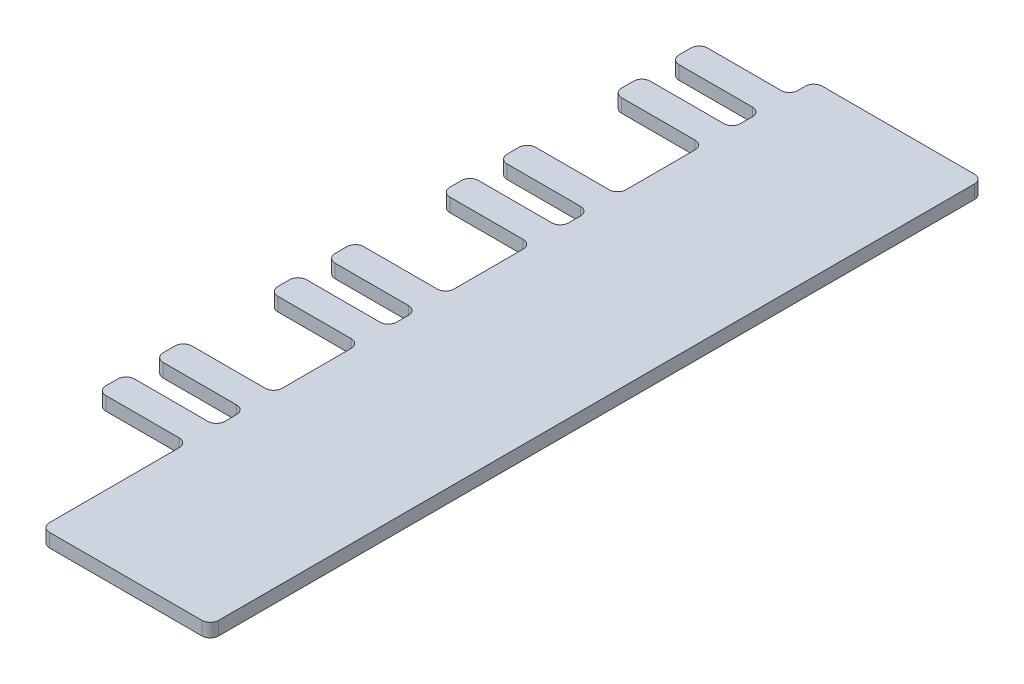
SolidWorks part; units mm, degrees
ref_plane "Front Plane" through (0, 0, 0) normal (0, 0, 1) x (1, 0, 0)
ref_plane "Top Plane" through (0, 0, 0) normal (0, 1, 0) x (1, 0, 0)
ref_plane "Right Plane" through (0, 0, 0) normal (1, 0, 0) x (0, 0, -1)
sketch "Sketch1" plane through (0, 0, 0) normal (0, 1, 0) x (1, 0, 0)
  line L0 (-0.75, 13) -> (-7.25, 13)
  line L2 (0, 12.25) -> (0, 0.75)
  line L5 (-8, 14.27) -> (5.7163, 14.27) construction
  line L7 (-8, 13.75) -> (-8, 14.79)
  line L8 (-7.25, 15.54) -> (-0.7462, 15.54)
  line L12 (0, 17.33) -> (0, 16.2149)
  line L17 (-0.75, 18.08) -> (-7.25, 18.08)
  line L22 (-8, 18.83) -> (-8, 19.87)
  line L27 (-7.25, 20.62) -> (-0.7462, 20.62)
  line L56 (14.25, 0) -> (0.75, 0)
  line L84 (0, 22.41) -> (0, 10.91) [skipped]
  line L85 (-0.75, 23.16) -> (-7.25, 23.16) [skipped]
  line L86 (-8, 23.91) -> (-8, 24.95) [skipped]
  line L87 (-7.25, 25.7) -> (-0.7462, 25.7) [skipped]
  line L88 (0, 27.49) -> (0, 15.99) [skipped]
  line L89 (-0.75, 28.24) -> (-7.25, 28.24) [skipped]
  line L90 (-8, 28.99) -> (-8, 30.03) [skipped]
  line L91 (-7.25, 30.78) -> (-0.7462, 30.78) [skipped]
  line L92 (0, 32.57) -> (0, 21.07) [skipped]
  line L93 (-0.75, 33.32) -> (-7.25, 33.32) [skipped]
  line L94 (-8, 34.07) -> (-8, 35.11) [skipped]
  line L95 (-7.25, 35.86) -> (-0.7462, 35.86) [skipped]
  line L96 (0, 37.65) -> (0, 26.15) [skipped]
  line L97 (-0.75, 38.4) -> (-7.25, 38.4) [skipped]
  line L98 (-8, 39.15) -> (-8, 40.19) [skipped]
  line L99 (-7.25, 40.94) -> (-0.7462, 40.94) [skipped]
  line L100 (0, 42.73) -> (0, 31.23) [skipped]
  line L101 (-0.75, 43.48) -> (-7.25, 43.48) [skipped]
  line L102 (-8, 44.23) -> (-8, 45.27) [skipped]
  line L103 (-7.25, 46.02) -> (-0.7462, 46.02) [skipped]
  line L104 (0, 47.81) -> (0, 36.31) [skipped]
  line L105 (-0.75, 48.56) -> (-7.25, 48.56) [skipped]
  line L106 (-8, 49.31) -> (-8, 50.35) [skipped]
  line L107 (-7.25, 51.1) -> (-0.7462, 51.1) [skipped]
  line L108 (0, 52.89) -> (0, 41.39) [skipped]
  line L109 (-0.75, 53.64) -> (-7.25, 53.64) [skipped]
  line L110 (-8, 54.39) -> (-8, 55.43) [skipped]
  line L111 (-7.25, 56.18) -> (-0.7462, 56.18) [skipped]
  line L112 (0, 57.97) -> (0, 46.47) [skipped]
  line L113 (-0.75, 58.72) -> (-7.25, 58.72) [skipped]
  line L114 (-8, 59.47) -> (-8, 60.51) [skipped]
  line L115 (-7.25, 61.26) -> (-0.7462, 61.26) [skipped]
  line L116 (-0.75, 28.24) -> (-7.25, 28.24)
  line L117 (-8, 28.99) -> (-8, 30.03)
  line L118 (-7.25, 30.78) -> (-0.7462, 30.78)
  line L119 (0, 32.57) -> (0, 31.4549)
  line L120 (-0.75, 33.32) -> (-7.25, 33.32)
  line L121 (-8, 34.07) -> (-8, 35.11)
  line L122 (-7.25, 35.86) -> (-0.7462, 35.86)
  line L123 (-0.75, 43.48) -> (-7.25, 43.48)
  line L124 (-8, 44.23) -> (-8, 45.27)
  line L125 (-7.25, 46.02) -> (-0.7462, 46.02)
  line L126 (0, 47.81) -> (0, 46.6949)
  line L127 (-0.75, 48.56) -> (-7.25, 48.56)
  line L128 (-8, 49.31) -> (-8, 50.35)
  line L129 (-7.25, 51.1) -> (-0.7462, 51.1)
  line L130 (-0.75, 58.72) -> (-7.25, 58.72)
  line L131 (-8, 59.47) -> (-8, 60.51)
  line L132 (-7.25, 61.26) -> (-0.7462, 61.26)
  line L133 (0, 63.05) -> (0, 61.9349)
  line L134 (-0.75, 63.8) -> (-7.25, 63.8)
  line L135 (-8, 64.55) -> (-8, 65.59)
  line L136 (-7.25, 66.34) -> (-0.7462, 66.34)
  line L137 (0, 27.49) -> (0, 21.2949)
  line L138 (0, 36.5349) -> (0, 42.73)
  line L139 (0, 51.7749) -> (0, 57.97)
  line L140 (0, 67.0149) -> (0, 67.74)
  line L141 (0.75, 68.49) -> (14.25, 68.49)
  line L142 (15, 67.74) -> (15, 0.75)
  arc A0 (-0.7462, 15.54) -> (0, 16.2149) centre (-0.7462, 16.29) ccw
  arc A1 (-8, 14.79) -> (-7.25, 15.54) centre (-7.25, 14.79) cw
  arc A2 (-7.25, 13) -> (-8, 13.75) centre (-7.25, 13.75) cw
  arc A3 (0, 0.75) -> (0.75, 0) centre (0.75, 0.75) ccw
  arc A4 (-0.75, 13) -> (0, 12.25) centre (-0.75, 12.25) cw
  arc A5 (15, 0.75) -> (14.25, 0) centre (14.25, 0.75) cw
  arc A6 (-0.75, 18.08) -> (0, 17.33) centre (-0.75, 17.33) cw
  arc A7 (-7.25, 18.08) -> (-8, 18.83) centre (-7.25, 18.83) cw
  arc A8 (-8, 19.87) -> (-7.25, 20.62) centre (-7.25, 19.87) cw
  arc A9 (-0.7462, 20.62) -> (0, 21.2949) centre (-0.7462, 21.37) ccw
  arc A44 (-0.75, 23.16) -> (0, 22.41) centre (-0.75, 22.41) cw [skipped]
  arc A45 (-7.25, 23.16) -> (-8, 23.91) centre (-7.25, 23.91) cw [skipped]
  arc A46 (-8, 24.95) -> (-7.25, 25.7) centre (-7.25, 24.95) cw [skipped]
  arc A47 (-0.7462, 25.7) -> (0, 26.3749) centre (-0.7462, 26.45) ccw [skipped]
  arc A48 (-0.75, 28.24) -> (0, 27.49) centre (-0.75, 27.49) cw [skipped]
  arc A49 (-7.25, 28.24) -> (-8, 28.99) centre (-7.25, 28.99) cw [skipped]
  arc A50 (-8, 30.03) -> (-7.25, 30.78) centre (-7.25, 30.03) cw [skipped]
  arc A51 (-0.7462, 30.78) -> (0, 31.4549) centre (-0.7462, 31.53) ccw [skipped]
  arc A52 (-0.75, 33.32) -> (0, 32.57) centre (-0.75, 32.57) cw [skipped]
  arc A53 (-7.25, 33.32) -> (-8, 34.07) centre (-7.25, 34.07) cw [skipped]
  arc A54 (-8, 35.11) -> (-7.25, 35.86) centre (-7.25, 35.11) cw [skipped]
  arc A55 (-0.7462, 35.86) -> (0, 36.5349) centre (-0.7462, 36.61) ccw [skipped]
  arc A56 (-0.75, 38.4) -> (0, 37.65) centre (-0.75, 37.65) cw [skipped]
  arc A57 (-7.25, 38.4) -> (-8, 39.15) centre (-7.25, 39.15) cw [skipped]
  arc A58 (-8, 40.19) -> (-7.25, 40.94) centre (-7.25, 40.19) cw [skipped]
  arc A59 (-0.7462, 40.94) -> (0, 41.6149) centre (-0.7462, 41.69) ccw [skipped]
  arc A60 (-0.75, 43.48) -> (0, 42.73) centre (-0.75, 42.73) cw [skipped]
  arc A61 (-7.25, 43.48) -> (-8, 44.23) centre (-7.25, 44.23) cw [skipped]
  arc A62 (-8, 45.27) -> (-7.25, 46.02) centre (-7.25, 45.27) cw [skipped]
  arc A63 (-0.7462, 46.02) -> (0, 46.6949) centre (-0.7462, 46.77) ccw [skipped]
  arc A64 (-0.75, 48.56) -> (0, 47.81) centre (-0.75, 47.81) cw [skipped]
  arc A65 (-7.25, 48.56) -> (-8, 49.31) centre (-7.25, 49.31) cw [skipped]
  arc A66 (-8, 50.35) -> (-7.25, 51.1) centre (-7.25, 50.35) cw [skipped]
  arc A67 (-0.7462, 51.1) -> (0, 51.7749) centre (-0.7462, 51.85) ccw [skipped]
  arc A68 (-0.75, 53.64) -> (0, 52.89) centre (-0.75, 52.89) cw [skipped]
  arc A69 (-7.25, 53.64) -> (-8, 54.39) centre (-7.25, 54.39) cw [skipped]
  arc A70 (-8, 55.43) -> (-7.25, 56.18) centre (-7.25, 55.43) cw [skipped]
  arc A71 (-0.7462, 56.18) -> (0, 56.8549) centre (-0.7462, 56.93) ccw [skipped]
  arc A72 (-0.75, 58.72) -> (0, 57.97) centre (-0.75, 57.97) cw [skipped]
  arc A73 (-7.25, 58.72) -> (-8, 59.47) centre (-7.25, 59.47) cw [skipped]
  arc A74 (-8, 60.51) -> (-7.25, 61.26) centre (-7.25, 60.51) cw [skipped]
  arc A75 (-0.7462, 61.26) -> (0, 61.9349) centre (-0.7462, 62.01) ccw [skipped]
  arc A76 (-0.7462, 30.78) -> (0, 31.4549) centre (-0.7462, 31.53) ccw
  arc A77 (-8, 30.03) -> (-7.25, 30.78) centre (-7.25, 30.03) cw
  arc A78 (-7.25, 28.24) -> (-8, 28.99) centre (-7.25, 28.99) cw
  arc A79 (-0.75, 28.24) -> (0, 27.49) centre (-0.75, 27.49) cw
  arc A80 (-0.75, 33.32) -> (0, 32.57) centre (-0.75, 32.57) cw
  arc A81 (-7.25, 33.32) -> (-8, 34.07) centre (-7.25, 34.07) cw
  arc A82 (-8, 35.11) -> (-7.25, 35.86) centre (-7.25, 35.11) cw
  arc A83 (-0.7462, 35.86) -> (0, 36.5349) centre (-0.7462, 36.61) ccw
  arc A84 (-0.7462, 46.02) -> (0, 46.6949) centre (-0.7462, 46.77) ccw
  arc A85 (-8, 45.27) -> (-7.25, 46.02) centre (-7.25, 45.27) cw
  arc A86 (-7.25, 43.48) -> (-8, 44.23) centre (-7.25, 44.23) cw
  arc A87 (-0.75, 43.48) -> (0, 42.73) centre (-0.75, 42.73) cw
  arc A88 (-0.75, 48.56) -> (0, 47.81) centre (-0.75, 47.81) cw
  arc A89 (-7.25, 48.56) -> (-8, 49.31) centre (-7.25, 49.31) cw
  arc A90 (-8, 50.35) -> (-7.25, 51.1) centre (-7.25, 50.35) cw
  arc A91 (-0.7462, 51.1) -> (0, 51.7749) centre (-0.7462, 51.85) ccw
  arc A92 (-0.7462, 61.26) -> (0, 61.9349) centre (-0.7462, 62.01) ccw
  arc A93 (-8, 60.51) -> (-7.25, 61.26) centre (-7.25, 60.51) cw
  arc A94 (-7.25, 58.72) -> (-8, 59.47) centre (-7.25, 59.47) cw
  arc A95 (-0.75, 58.72) -> (0, 57.97) centre (-0.75, 57.97) cw
  arc A96 (-0.75, 63.8) -> (0, 63.05) centre (-0.75, 63.05) cw
  arc A97 (-7.25, 63.8) -> (-8, 64.55) centre (-7.25, 64.55) cw
  arc A98 (-8, 65.59) -> (-7.25, 66.34) centre (-7.25, 65.59) cw
  arc A99 (-0.7462, 66.34) -> (0, 67.0149) centre (-0.7462, 67.09) ccw
  arc A100 (0, 67.74) -> (0.75, 68.49) centre (0.75, 67.74) cw
  arc A101 (14.25, 68.49) -> (15, 67.74) centre (14.25, 67.74) cw
  point P0 (0, 0)
  point P27 (0, 15.54)
  point P46 (0, 30.78)
  point P48 (-8, 15.54)
  point P69 (-8, 13)
  point P73 (0, 46.02)
  point P78 (0, 0)
  point P81 (0, 13)
  point P84 (15, 0)
  point P108 (0, 61.26)
  point P121 (0, 0)
  point P122 (-0.7462, 16.2149)
  point P123 (-3.9981, 66.34)
  dimension "D6" = 0.75
  dimension "D7" = 0.75
  dimension "D8" = 4
  dimension "D9" = 10.16
  dimension "D11" = 0.75
  dimension "D1" = 2.54
  dimension "D2" = 8
  dimension "D3" = 10
  dimension "D4" = 13
  dimension "D5" = 15
  dimension "D10" = 5.08
  dimension "D12" = 2.15
extrude "Boss-Extrude1" add sketch "Sketch1" along normal blind 1.2
